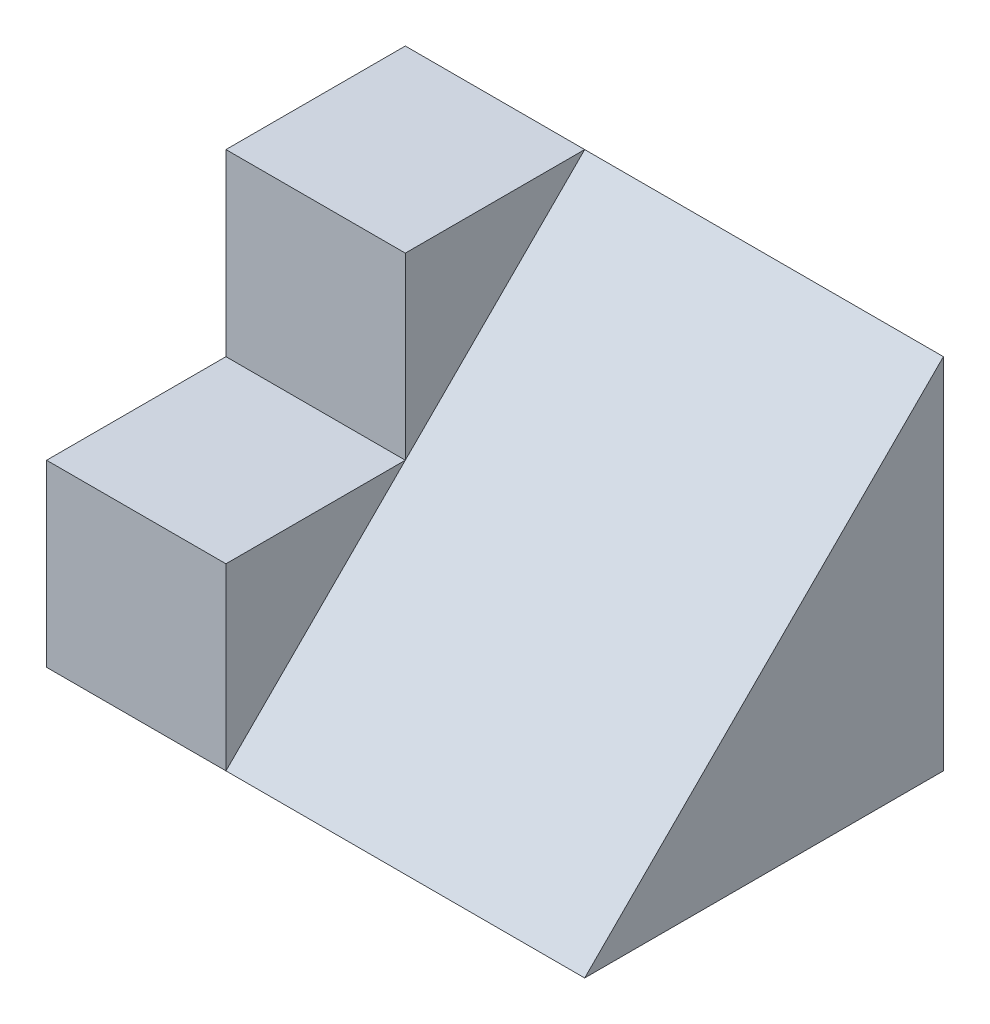
SolidWorks part; units mm, degrees
ref_plane "Front Plane" through (0, 0, 0) normal (0, 0, 1) x (1, 0, 0)
ref_plane "Top Plane" through (0, 0, 0) normal (0, 1, 0) x (1, 0, 0)
ref_plane "Right Plane" through (0, 0, 0) normal (1, 0, 0) x (0, 0, -1)
sketch "Sketch2" plane through (0, 0, 0) normal (0, 0, 1) x (1, 0, 0)
  line L1 (-76.2, -50.8) -> (76.2, -50.8)
  line L2 (-76.2, -50.8) -> (-76.2, 50.8)
  line L3 (-76.2, 50.8) -> (76.2, 50.8)
  line L4 (76.2, -50.8) -> (76.2, 50.8)
  line L5 (-76.2, -50.8) -> (76.2, 50.8) construction
  line L6 (-76.2, 50.8) -> (76.2, -50.8) construction
  point P0 (0, 0)
  dimension "D1" = 152.4
  dimension "D2" = 101.6
extrude "Boss-Extrude1" add sketch "Sketch2" along normal mid plane 101.6
sketch "Sketch3" plane through (0, 50.8, 0) normal (0, 1, 0) x (1, 0, 0)
  line L1 (-76.2, -50.8) -> (-25.4, -50.8)
  line L2 (-76.2, -50.8) -> (-76.2, 0)
  line L3 (-76.2, 0) -> (-25.4, 0)
  line L4 (-25.4, -50.8) -> (-25.4, 0)
  dimension "D1" = 50.8
  dimension "D2" = 50.8
extrude "Cut-Extrude1" cut sketch "Sketch3" against normal blind 50.8
sketch "Sketch4" plane through (76.2, 0, 0) normal (1, 0, 0) x (0, 0, -1)
  line L0 (-50.8, -50.8) -> (50.8, 50.8)
  line L1 (50.8, 50.8) -> (-50.8, 50.8)
  line L2 (-50.8, 50.8) -> (-50.8, -50.8)
extrude "Cut-Extrude2" cut sketch "Sketch4" against normal blind 101.6 contours L2 L0 L1
